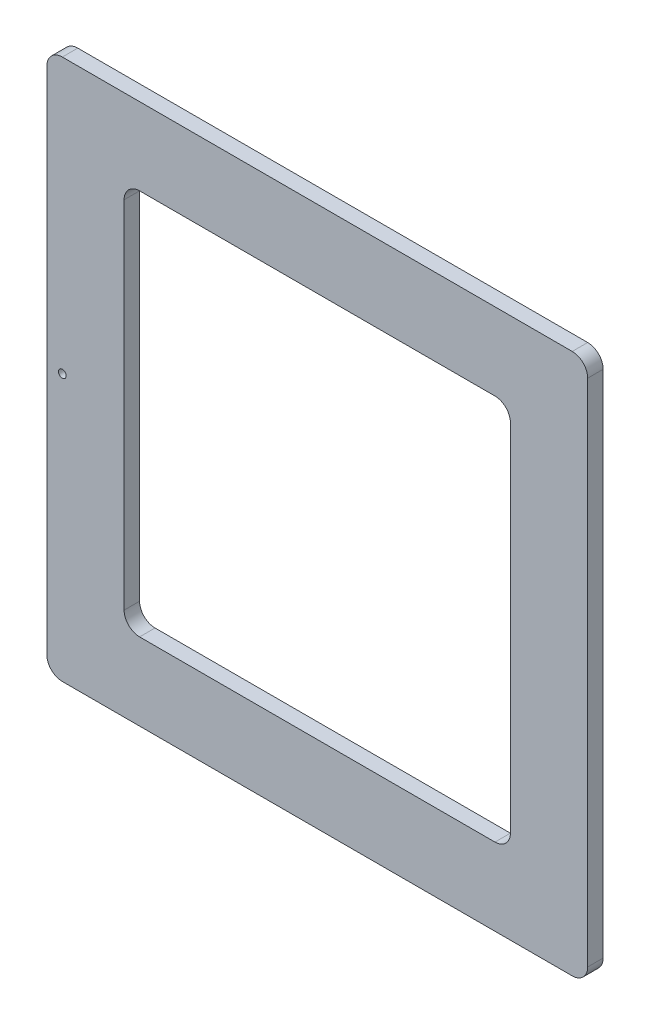
SolidWorks part; units mm, degrees
ref_plane "Спереди" through (0, 0, 0) normal (0, 0, 1) x (1, 0, 0)
ref_plane "Сверху" through (0, 0, 0) normal (0, 1, 0) x (1, 0, 0)
ref_plane "Справа" through (0, 0, 0) normal (1, 0, 0) x (0, 0, -1)
sketch "Эскиз1" plane through (0, 0, 0) normal (0, 0, 1) x (1, 0, 0)
  line L1 (33, -35) -> (-33, -35)
  line L2 (35, -33) -> (35, 33)
  line L3 (33, 35) -> (-33, 35)
  line L4 (-35, -33) -> (-35, 33)
  line L5 (23, -25) -> (-23, -25)
  line L6 (25, -23) -> (25, 23)
  line L7 (23, 25) -> (-23, 25)
  line L8 (-25, -23) -> (-25, 23)
  arc A0 (33, 35) -> (35, 33) centre (33, 33) cw
  arc A1 (-35, 33) -> (-33, 35) centre (-33, 33) cw
  arc A2 (-33, -35) -> (-35, -33) centre (-33, -33) cw
  arc A3 (35, -33) -> (33, -35) centre (33, -33) cw
  arc A4 (25, -23) -> (23, -25) centre (23, -23) cw
  arc A5 (23, 25) -> (25, 23) centre (23, 23) cw
  arc A6 (-23, 25) -> (-25, 23) centre (-23, 23) ccw
  arc A7 (-23, -25) -> (-25, -23) centre (-23, -23) cw
  point P0 (0, 0)
  point P6 (0, 0)
  point P13 (-15.4119, 35)
  point P14 (35, 35)
  point P17 (-35, 35)
  point P20 (-35, -35)
  dimension "D5" = 2
  dimension "D6" = 2
  dimension "D7" = 2
  dimension "D8" = 2
  dimension "D9" = 2
  dimension "D1" = 70
  dimension "D2" = 70
extrude "Бобышка-Вытянуть1" add sketch "Эскиз1" along normal blind 2
sketch "Эскиз2" plane through (0, 0, 0) normal (0, 0, 1) x (1, 0, 0)
  line L0 (-35, 33) -> (-35, -33) construction
  line L1 (33, 35) -> (-33, 35) construction
  circle A0 centre (-33, -0.5) radius 0.5
  dimension "D1" = 1
  dimension "D2" = 2
  dimension "D3" = 35.5
extrude "Вырез-Вытянуть3" cut sketch "Эскиз2" along normal blind 2
